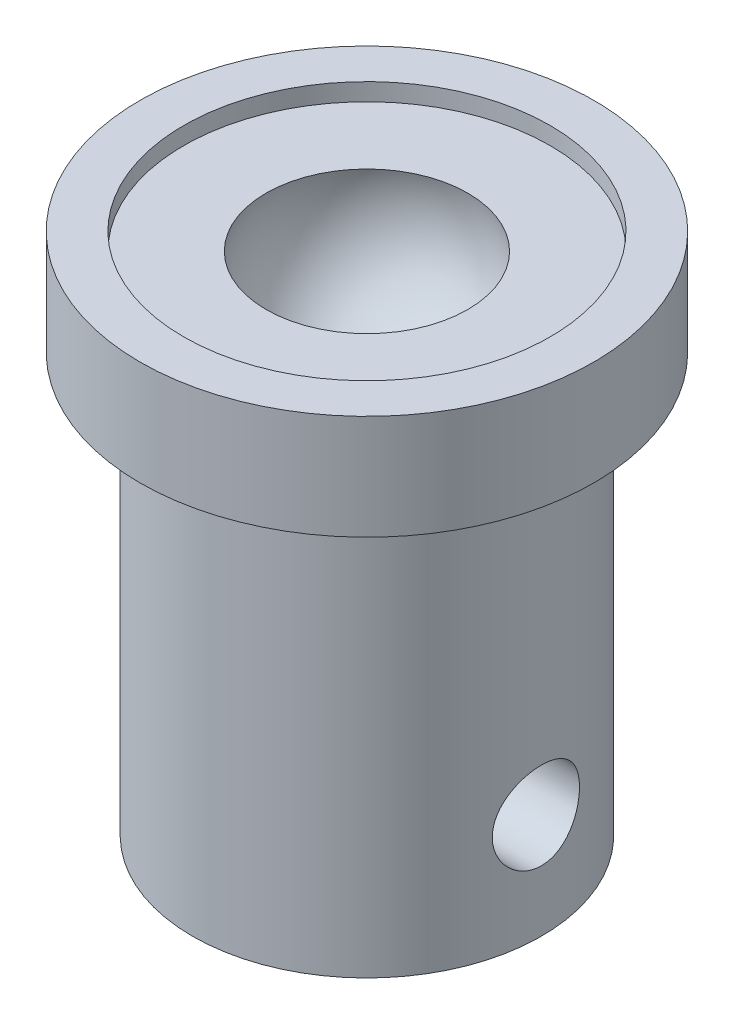
SolidWorks part; units mm, degrees
ref_plane "前视基准面" through (0, 0, 0) normal (0, 0, 1) x (1, 0, 0)
ref_plane "上视基准面" through (0, 0, 0) normal (0, 1, 0) x (1, 0, 0)
ref_plane "右视基准面" through (0, 0, 0) normal (1, 0, 0) x (0, 0, -1)
sketch "草图1" plane through (0, 0, 0) normal (0, 1, 0) x (1, 0, 0)
  circle A0 centre (0, 0) radius 10
  dimension "D1" = 20
extrude "凸台-拉伸1" add sketch "草图1" along normal blind 30
sketch "草图2" plane through (0, 30, 0) normal (0, 1, 0) x (1, 0, 0)
  circle A0 centre (0, 0) radius 13
  dimension "D1" = 26
extrude "凸台-拉伸2" add sketch "草图2" against normal blind 6
sketch "草图3" plane through (0, 0, 0) normal (1, 0, 0) x (0, 0, -1)
  circle A0 centre (0, 6) radius 2.5
  dimension "D1" = 5
  dimension "D2" = 6
extrude "切除-拉伸1" cut sketch "草图3" against normal through all and the other way through all
sketch "草图4" plane through (0, 0, 0) normal (0, -1, 0) x (-1, 0, 0)
  line L1 (-4.5, -4.5) -> (4.5, -4.5)
  line L2 (-4.5, -4.5) -> (-4.5, 4.5)
  line L3 (-4.5, 4.5) -> (4.5, 4.5)
  line L4 (4.5, -4.5) -> (4.5, 4.5)
  line L5 (-4.5, -4.5) -> (4.5, 4.5) construction
  line L6 (-4.5, 4.5) -> (4.5, -4.5) construction
  point P0 (0, 0)
  dimension "D1" = 9
  dimension "D2" = 9
extrude "切除-拉伸2" cut sketch "草图4" against normal blind 15
sketch "草图5" plane through (0, 0, 0) normal (0, 0, 1) x (1, 0, 0)
  line L0 (0, 37.8838) -> (0, -9.8343) construction
  line L1 (0, 33.3943) -> (0, 21.3943)
  arc A0 (0, 33.3943) -> (0, 21.3943) centre (0, 27.3943) cw
  point P6 (0, 27.3943)
  dimension "D1" = 6
revolve "切除-旋转1" cut sketch "草图5" angle 360 about L0
sketch "草图6" plane through (0, 30, 0) normal (0, 1, 0) x (1, 0, 0)
  circle A0 centre (0, 0) radius 10.5
  dimension "D1" = 21
extrude "切除-拉伸3" cut sketch "草图6" against normal blind 1
